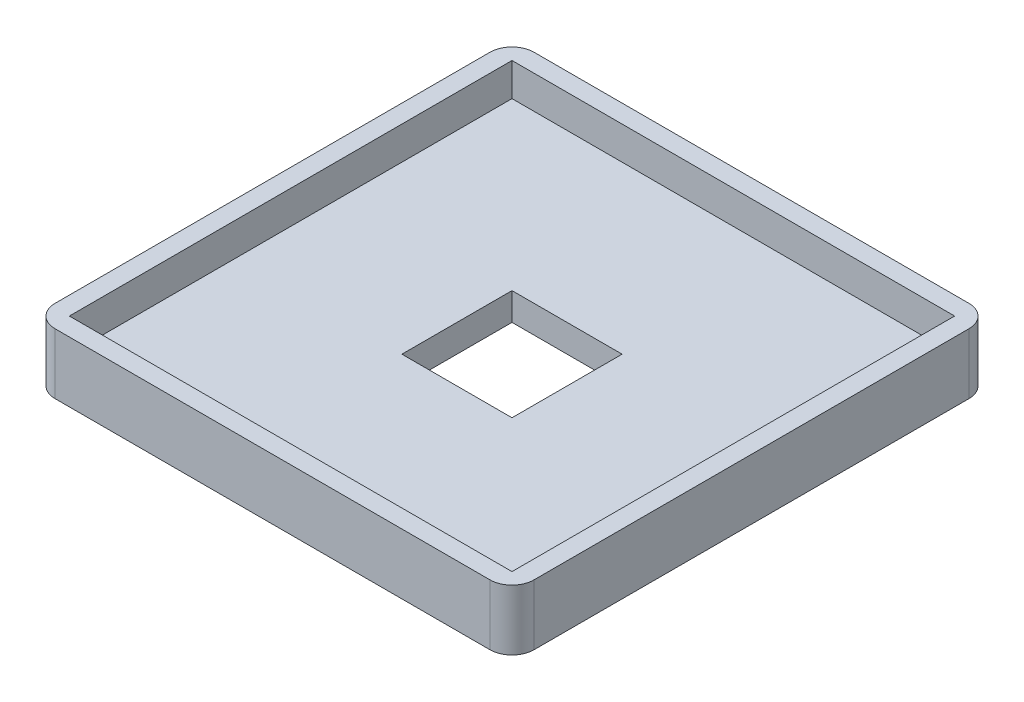
SolidWorks part; units mm, degrees
ref_plane "Front Plane" through (0, 0, 0) normal (0, 0, 1) x (1, 0, 0)
ref_plane "Top Plane" through (0, 0, 0) normal (0, 1, 0) x (1, 0, 0)
ref_plane "Right Plane" through (0, 0, 0) normal (1, 0, 0) x (0, 0, -1)
sketch "Sketch1" plane through (0, 0, 0) normal (0, 1, 0) x (1, 0, 0)
  line L1 (-21.75, 21.75) -> (21.75, 21.75)
  line L2 (-21.75, 21.75) -> (-21.75, -21.75)
  line L3 (-21.75, -21.75) -> (21.75, -21.75)
  line L4 (21.75, 21.75) -> (21.75, -21.75)
  line L5 (-21.75, 21.75) -> (21.75, -21.75) construction
  line L6 (-21.75, -21.75) -> (21.75, 21.75) construction
  point P0 (0, 0)
  dimension "D1" = 43.5
  dimension "D2" = 43.5
extrude "Boss-Extrude2" add sketch "Sketch1" along normal blind 2.5
sketch "Sketch3" plane through (0, 2.5, 0) normal (0, 1, 0) x (1, 0, 0)
  line L1 (-20.1, 20.1) -> (20.1, 20.1)
  line L2 (-20.1, 20.1) -> (-20.1, -20.1)
  line L3 (-20.1, -20.1) -> (20.1, -20.1)
  line L4 (20.1, 20.1) -> (20.1, -20.1)
  line L5 (-20.1, 20.1) -> (20.1, -20.1) construction
  line L6 (-20.1, -20.1) -> (20.1, 20.1) construction
  line L7 (-21.75, 21.75) -> (21.75, 21.75)
  line L8 (-21.75, 21.75) -> (-21.75, -21.75)
  line L9 (-21.75, -21.75) -> (21.75, -21.75)
  line L10 (21.75, 21.75) -> (21.75, -21.75)
  line L11 (-21.75, 21.75) -> (21.75, -21.75) construction
  line L12 (-21.75, -21.75) -> (21.75, 21.75) construction
  point P0 (0, 0)
  point P6 (0, 0)
  dimension "D1" = 40.2
  dimension "D2" = 40.2
extrude "Boss-Extrude3" add sketch "Sketch3" along normal blind 3
sketch "Sketch4" plane through (0, 2.5, 0) normal (0, 1, 0) x (1, 0, 0)
  line L1 (-5, 5) -> (5, 5)
  line L2 (-5, 5) -> (-5, -5)
  line L3 (-5, -5) -> (5, -5)
  line L4 (5, 5) -> (5, -5)
  line L5 (-5, 5) -> (5, -5) construction
  line L6 (-5, -5) -> (5, 5) construction
  point P0 (0, 0)
  dimension "D1" = 10
  dimension "D2" = 10
extrude "Cut-Extrude1" cut sketch "Sketch4" against normal blind 5
fillet "Fillet1" radius 2 4 edges at (21.75, 2.75, -21.75) (21.75, 2.75, 21.75) (-21.75, 2.75, 21.75) (-21.75, 2.75, -21.75)
